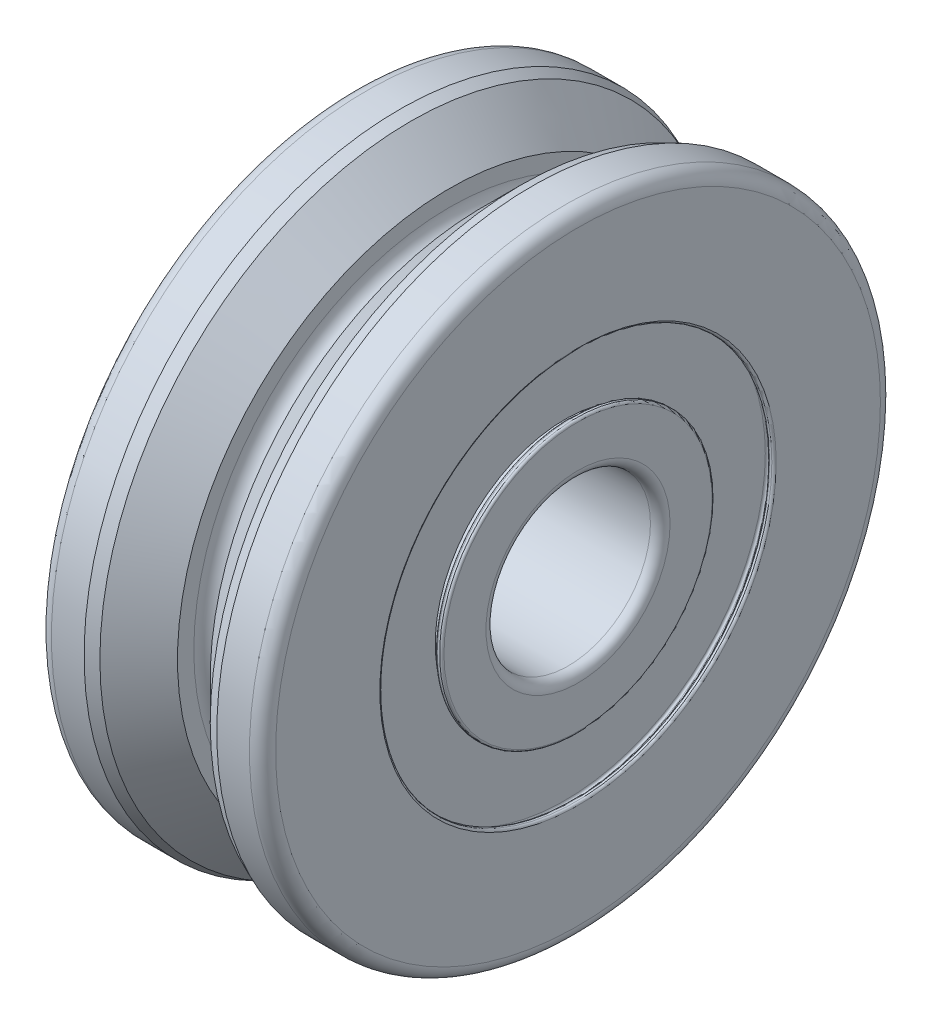
SolidWorks part; units mm, degrees
material "Plain Carbon Steel"
ref_plane "Front Plane" through (0, 0, 0) normal (0, 0, 1) x (1, 0, 0)
ref_plane "Top Plane" through (0, 0, 0) normal (0, 1, 0) x (1, 0, 0)
ref_plane "Right Plane" through (0, 0, 0) normal (1, 0, 0) x (0, 0, -1)
sketch "Sketch1" plane through (0, 0, 0) normal (0, 0, 1) x (1, 0, 0)
  line L0 (-3.4798, 4.1614) -> (-3.4798, 2.8575)
  line L1 (-3.175, 2.5527) -> (3.175, 2.5527)
  line L2 (3.4798, 2.8575) -> (3.4798, 4.1614)
  line L3 (3.4121, 4.2291) -> (3.3443, 4.2291)
  line L4 (3.2766, 4.1614) -> (3.2766, 4.0259)
  line L5 (3.2766, 4.0259) -> (3.0734, 4.0259)
  line L6 (3.0734, 4.0259) -> (3.0734, 6.2188)
  line L7 (3.1411, 6.2865) -> (3.2766, 6.2865)
  line L8 (3.2766, 6.2865) -> (3.2766, 6.151)
  line L9 (3.3443, 6.0833) -> (3.4121, 6.0833)
  line L10 (3.4798, 6.151) -> (3.4798, 9.3853)
  line L11 (3.0734, 9.7917) -> (2.0593, 9.7917)
  line L12 (2.0593, 9.7917) -> (1.7125, 9.648)
  line L13 (1.7125, 9.648) -> (0.508, 8.4436)
  line L14 (0.508, 8.4436) -> (0.508, 7.9375)
  line L15 (-0.508, 7.9375) -> (-0.508, 8.4436)
  line L16 (-0.508, 8.4436) -> (-1.7125, 9.648)
  line L17 (-1.7125, 9.648) -> (-2.0593, 9.7917)
  line L18 (-2.0593, 9.7917) -> (-3.0734, 9.7917)
  line L19 (-3.4798, 9.3853) -> (-3.4798, 6.151)
  line L20 (-3.4121, 6.0833) -> (-3.3443, 6.0833)
  line L21 (-3.2766, 6.151) -> (-3.2766, 6.2865)
  line L22 (-3.2766, 6.2865) -> (-3.1411, 6.2865)
  line L23 (-3.0734, 6.2188) -> (-3.0734, 4.0259)
  line L24 (-3.0734, 4.0259) -> (-3.2766, 4.0259)
  line L25 (-3.2766, 4.0259) -> (-3.2766, 4.1614)
  line L26 (-3.3443, 4.2291) -> (-3.4121, 4.2291)
  line L27 (-3.4798, 0) -> (3.4798, 0) construction
  arc A0 (-3.4121, 4.2291) -> (-3.4798, 4.1614) centre (-3.4121, 4.1614) ccw
  arc A1 (-3.4798, 2.8575) -> (-3.175, 2.5527) centre (-3.175, 2.8575) ccw
  arc A2 (3.175, 2.5527) -> (3.4798, 2.8575) centre (3.175, 2.8575) ccw
  arc A3 (3.4798, 4.1614) -> (3.4121, 4.2291) centre (3.4121, 4.1614) ccw
  arc A4 (3.3443, 4.2291) -> (3.2766, 4.1614) centre (3.3443, 4.1614) ccw
  arc A5 (3.0734, 6.2188) -> (3.1411, 6.2865) centre (3.1411, 6.2188) cw
  arc A6 (3.2766, 6.151) -> (3.3443, 6.0833) centre (3.3443, 6.151) ccw
  arc A7 (3.4121, 6.0833) -> (3.4798, 6.151) centre (3.4121, 6.151) ccw
  arc A8 (3.4798, 9.3853) -> (3.0734, 9.7917) centre (3.0734, 9.3853) ccw
  arc A9 (0.508, 7.9375) -> (-0.508, 7.9375) centre (0, 7.9375) cw
  arc A10 (-3.0734, 9.7917) -> (-3.4798, 9.3853) centre (-3.0734, 9.3853) ccw
  arc A11 (-3.4798, 6.151) -> (-3.4121, 6.0833) centre (-3.4121, 6.151) ccw
  arc A12 (-3.3443, 6.0833) -> (-3.2766, 6.151) centre (-3.3443, 6.151) ccw
  arc A13 (-3.1411, 6.2865) -> (-3.0734, 6.2188) centre (-3.1411, 6.2188) cw
  arc A14 (-3.2766, 4.1614) -> (-3.3443, 4.2291) centre (-3.3443, 4.1614) ccw
revolve "Revolve1" add sketch "Sketch1" angle 360 about L27
